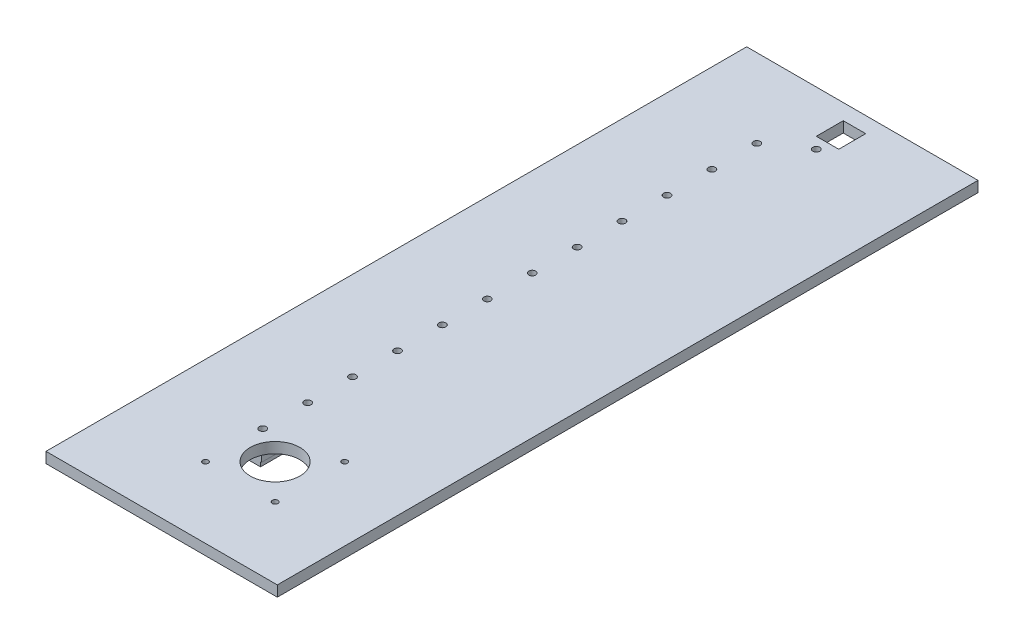
SolidWorks part; units mm, degrees
ref_plane "Front Plane" through (0, 0, 0) normal (0, 0, 1) x (1, 0, 0)
ref_plane "Top Plane" through (0, 0, 0) normal (0, 1, 0) x (1, 0, 0)
ref_plane "Right Plane" through (0, 0, 0) normal (1, 0, 0) x (0, 0, -1)
sketch "Sketch1" plane through (0, 0, 0) normal (0, 0, 1) x (1, 0, 0)
  line L1 (0, 0) -> (9, 0)
  line L2 (0, 0) -> (0, 5.5)
  line L3 (0, 5.5) -> (9, 5.5)
  line L4 (9, 0) -> (9, 5.5)
  line L5 (0, 0) -> (0.5, 0)
  line L6 (0, 0) -> (0, 2)
  line L7 (0, 2) -> (0.5, 2)
  line L8 (0.5, 0) -> (0.5, 2)
  line L9 (9, 0) -> (8.5, 0)
  line L10 (9, 0) -> (9, 2)
  line L11 (9, 2) -> (8.5, 2)
  line L12 (8.5, 0) -> (8.5, 2)
  dimension "D1" = 5.5
  dimension "D2" = 9
  dimension "D3" = 2
  dimension "D4" = 0.5
  dimension "D5" = 0.5
  dimension "D6" = 2
extrude "Boss-Extrude2" add sketch "Sketch1" along normal blind 230 contours L1 L12 L11 L4 L3 L2 L7 L8
sketch "Sketch2" plane through (0, 0, 0) normal (0, -1, 0) x (-1, 0, 0)
  line L0 (-0.5, -230) -> (-8.5, -230) construction
  line L2 (-4.5, -230) -> (-4.5, 0) construction
  line L3 (-0.5, 0) -> (-8.5, 0) construction
  circle A0 centre (-4.5, -225) radius 3
  dimension "D2" = 6
  dimension "D1" = 5
extrude "Cut-Extrude1" cut sketch "Sketch2" against normal blind 4
sketch "Sketch3" plane through (0, 4, 0) normal (0, -1, 0) x (-1, 0, 0)
  circle A0 centre (-4.5, -225) radius 1.55
  dimension "D1" = 3.1
extrude "Cut-Extrude2" cut sketch "Sketch3" against normal blind 4
pattern_linear "LPattern1" count 12 spacing 20 along (0, 0, -1) of "Cut-Extrude1", "Cut-Extrude2"
sketch "Sketch4" plane through (0, 5.5, 0) normal (0, 1, 0) x (1, 0, 0)
  line L0 (0, 0) -> (9, 0) construction
  line L1 (-35, 30) -> (68, 30)
  line L2 (-35, 30) -> (-35, -282)
  line L3 (-35, -282) -> (68, -282)
  line L4 (68, 30) -> (68, -282)
  line L5 (0, -230) -> (9, -230) construction
  line L6 (0, -230) -> (0, 0) construction
  line L7 (20, -235) -> (20, 19.9139) construction
  line L9 (25, 23) -> (15, 23)
  line L10 (25, 23) -> (25, 11)
  line L11 (25, 11) -> (15, 11)
  line L12 (15, 23) -> (15, 11)
  line L13 (25, 23) -> (15, 11) construction
  line L14 (25, 11) -> (15, 23) construction
  circle A0 centre (20, -235) radius 11.05
  circle A1 centre (20, 6) radius 1.55
  circle A2 centre (4.5, -5) radius 1.55 construction
  circle A3 centre (4.5, -25) radius 1.55 construction
  circle A4 centre (4.5, -45) radius 1.55 construction
  circle A5 centre (4.5, -65) radius 1.55 construction
  circle A6 centre (4.5, -85) radius 1.55 construction
  circle A7 centre (4.5, -105) radius 1.55 construction
  circle A8 centre (4.5, -125) radius 1.55 construction
  circle A9 centre (4.5, -145) radius 1.55 construction
  circle A10 centre (4.5, -165) radius 1.55 construction
  circle A11 centre (4.5, -185) radius 1.55 construction
  circle A12 centre (4.5, -205) radius 1.55 construction
  circle A13 centre (4.5, -225) radius 1.55 construction
  circle A14 centre (4.5, -225) radius 1.55
  circle A15 centre (4.5, -205) radius 1.55
  circle A16 centre (4.5, -185) radius 1.55
  circle A17 centre (4.5, -165) radius 1.55
  circle A18 centre (4.5, -145) radius 1.55
  circle A19 centre (4.5, -125) radius 1.55
  circle A20 centre (4.5, -105) radius 1.55
  circle A21 centre (4.5, -85) radius 1.55
  circle A22 centre (4.5, -65) radius 1.55
  circle A23 centre (4.5, -45) radius 1.55
  circle A24 centre (4.5, -25) radius 1.55
  circle A25 centre (4.5, -5) radius 1.55
  point P16 (20, 17)
  point P21 (20, 11)
  dimension "D7" = 22.1
  dimension "D11" = 5
  dimension "D12" = 3.1
  dimension "D1" = 312
  dimension "D2" = 30
  dimension "D3" = 103
  dimension "D4" = 35
  dimension "D5" = 5
  dimension "D6" = 20
  dimension "D8" = 241
  dimension "D9" = 12
  dimension "D10" = 10
extrude "Boss-Extrude3" add sketch "Sketch4" along normal blind 4.75
sketch "Sketch5" plane through (0, 10.25, 0) normal (0, 1, 0) x (1, 0, 0)
  line L4 (-35, 30) -> (-35, -282)
  line L5 (-35, -282) -> (68, -282)
  line L6 (68, -282) -> (68, 30)
  line L7 (68, 30) -> (-35, 30)
  line L8 (-35, 30) -> (-35, -282)
  line L9 (-35, -282) -> (68, -282)
  line L10 (68, -282) -> (68, 30)
  line L11 (68, 30) -> (-35, 30)
  circle A0 centre (35.5, -250.5) radius 1.25 construction
  circle A1 centre (4.5, -250.5) radius 1.25 construction
  circle A2 centre (35.5, -219.5) radius 1.25 construction
  circle A3 centre (4.5, -219.5) radius 1.25 construction
  circle A4 centre (35.5, -250.5) radius 1.25
  circle A5 centre (4.5, -250.5) radius 1.25
  circle A6 centre (35.5, -219.5) radius 1.25
  circle A7 centre (4.5, -219.5) radius 1.25
  point P16 (0, 0)
  point P17 (0, 0)
  point P18 (0, 0)
  dimension "D1" = 0
extrude "Cut-Extrude3" cut sketch "Sketch5" against normal blind 10 contours A4 | A6 | A5
